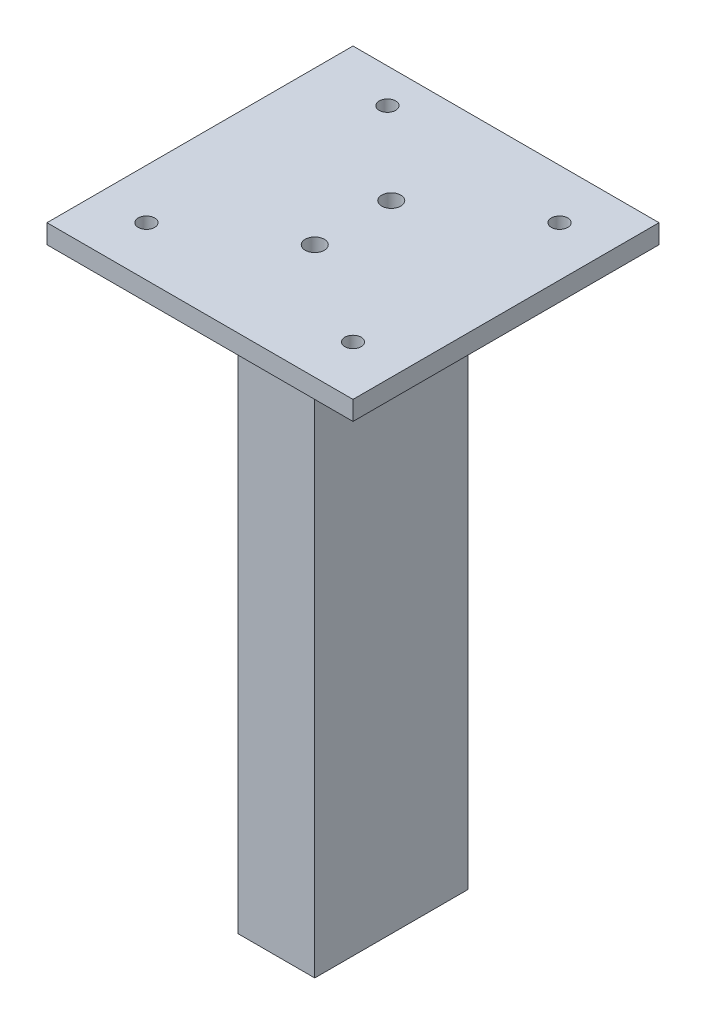
SolidWorks part; units mm, degrees
material "1060 Alloy"
ref_plane "Front Plane" through (0, 0, 0) normal (0, 0, 1) x (1, 0, 0)
ref_plane "Top Plane" through (0, 0, 0) normal (0, 1, 0) x (1, 0, 0)
ref_plane "Right Plane" through (0, 0, 0) normal (1, 0, 0) x (0, 0, -1)
sketch "Sketch1" plane through (0, 0, 0) normal (0, 1, 0) x (1, 0, 0)
  line L1 (-10, -20) -> (10, -20)
  line L2 (-10, -20) -> (-10, 20)
  line L3 (-10, 20) -> (10, 20)
  line L4 (10, -20) -> (10, 20)
  line L5 (-10, -20) -> (10, 20) construction
  line L6 (-10, 20) -> (10, -20) construction
  point P0 (0, 0)
  dimension "D1" = 40
  dimension "D2" = 20
extrude "Boss-Extrude1" add sketch "Sketch1" along normal blind 151
sketch "Sketch2" plane through (0, 151, 0) normal (0, 1, 0) x (1, 0, 0)
  line L1 (-40, -40) -> (40, -40)
  line L2 (-40, -40) -> (-40, 40)
  line L3 (-40, 40) -> (40, 40)
  line L4 (40, -40) -> (40, 40)
  line L5 (-40, -40) -> (40, 40) construction
  line L6 (-40, 40) -> (40, -40) construction
  point P0 (0, 0)
  dimension "D1" = 80
  dimension "D2" = 80
extrude "Boss-Extrude2" add sketch "Sketch2" along normal blind 5
sketch "Sketch3" plane through (0, 156, 0) normal (0, 1, 0) x (1, 0, 0)
  circle A0 centre (0, 10) radius 2.5
  circle A1 centre (0, -10) radius 2.5
  dimension "D1" = 5
  dimension "D2" = 20
  dimension "D3" = 10
extrude "Cut-Extrude1" cut sketch "Sketch3" against normal through all
sketch "Sketch4" plane through (0, 156, 0) normal (0, 1, 0) x (1, 0, 0)
  line L1 (-40, -40) -> (40, -40) construction
  line L2 (-40, 40) -> (-40, -40) construction
  line L3 (40, -40) -> (40, 40) construction
  line L4 (40, 40) -> (-40, 40) construction
  circle A0 centre (-22, 31) radius 2.15
  circle A1 centre (27, 27) radius 2.15
  circle A2 centre (-27, -27) radius 2.15
  circle A3 centre (27, -27) radius 2.15
  dimension "D5" = 4.3
  dimension "D1" = 9
  dimension "D2" = 13
  dimension "D3" = 13
  dimension "D4" = 13
  dimension "D6" = 18
  dimension "D7" = 13
extrude "Cut-Extrude2" cut sketch "Sketch4" against normal up to next
